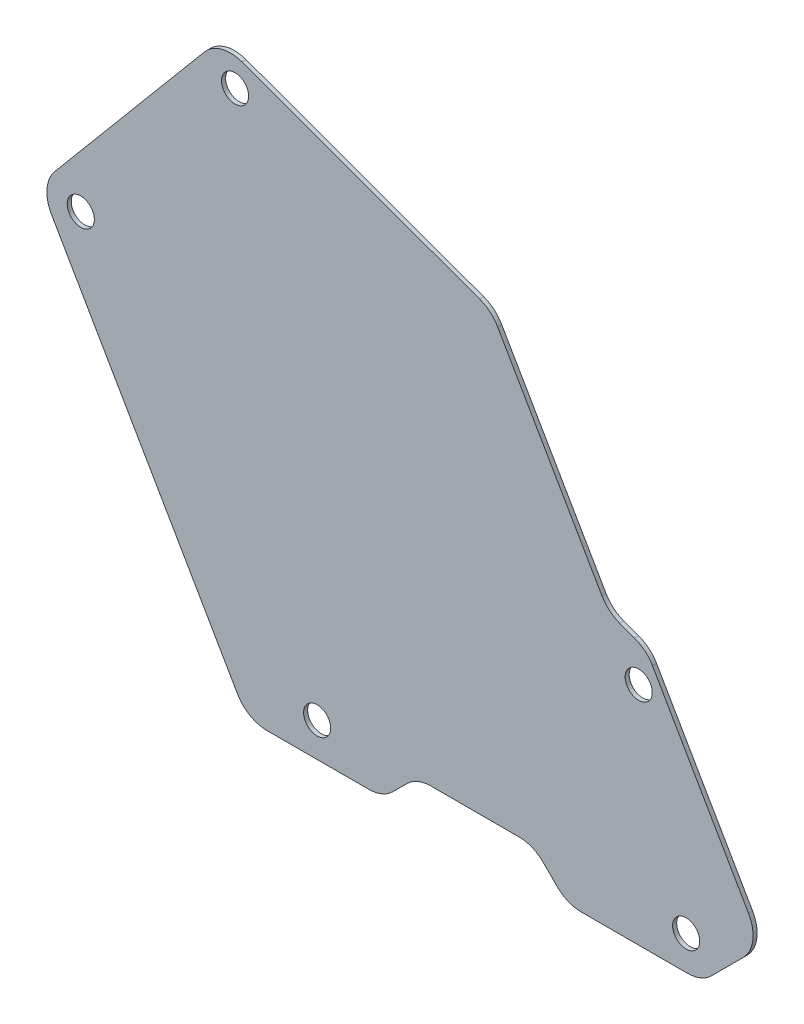
SolidWorks part; units mm, degrees
material "Vidro"
ref_plane "Plano frontal" through (0, 0, 0) normal (0, 0, 1) x (1, 0, 0)
ref_plane "Plano superior" through (0, 0, 0) normal (0, 1, 0) x (1, 0, 0)
ref_plane "Plano direito" through (0, 0, 0) normal (1, 0, 0) x (0, 0, -1)
sketch "Esboço1" plane through (0, 0, 0) normal (0, 0, 1) x (1, 0, 0)
  line L0 (-150, 259.8076) -> (0, 0)
  line L1 (-150, 259.8076) -> (-18.2285, 416.8467)
  line L2 (-23.2285, 418.6666) -> (177.0195, 345.7823)
  line L3 (169.71, 348.4427) -> (259.71, 192.5581)
  line L4 (259.71, 192.5581) -> (287.8295, 182.3235)
  line L5 (287.8295, 182.3235) -> (370, 40)
  line L6 (370, 40) -> (330, 0)
  line L7 (330, 0) -> (235, 0)
  line L8 (210, 25) -> (235, 0)
  line L9 (210, 25) -> (120, 25)
  line L10 (120, 25) -> (95, 0)
  line L11 (95, 0) -> (0, 0)
  line L12 (-156.0806, 260.3396) -> (-86.8301, 140.3942) construction
  line L13 (-150, 259.8076) -> (-80, 138.5641) construction
  line L14 (-18.2285, 416.8467) -> (169.71, 348.4427) construction
  line L16 (-19.8083, 422.7426) -> (173.1302, 352.5187)
  line L17 (173.1302, 352.5187) -> (263.1302, 196.6342)
  line L18 (263.1302, 196.6342) -> (291.2497, 186.3995)
  line L19 (291.2497, 186.3995) -> (376.2484, 39.1774)
  line L20 (376.2484, 39.1774) -> (332.0711, -5)
  line L21 (332.0711, -5) -> (232.9289, -5)
  line L22 (207.9289, 20) -> (232.9289, -5)
  line L23 (207.9289, 20) -> (122.0711, 20)
  line L24 (122.0711, 20) -> (97.0711, -5)
  line L25 (97.0711, -5) -> (-2.8868, -5)
  line L30 (-156.0806, 260.3396) -> (-2.8868, -5)
  line L31 (-156.0806, 260.3396) -> (-19.8083, 422.7426)
  line L32 (-80, 138.5641) -> (-80.433, 138.3141) construction
  line L33 (-80.433, 138.3141) -> (-15.433, 25.7308) construction
  line L34 (-15.433, 25.7308) -> (-15, 25.9808) construction
  line L35 (-17.2631, 18.9006) -> (-16.8301, 19.1506) construction
  line L36 (-87.2631, 140.1442) -> (-17.2631, 18.9006) construction
  line L37 (-86.8301, 140.3942) -> (-87.2631, 140.1442) construction
  line L38 (-15, 25.9808) -> (0, 0) construction
  line L39 (-16.8301, 19.1506) -> (-2.8868, -5) construction
  dimension "D1" = 110
  dimension "D2" = 110
  dimension "D3" = 120
  dimension "D4" = 135
  dimension "D5" = 300
  dimension "D6" = 205
  dimension "D7" = 200
  dimension "D8" = 180
  dimension "D9" = 330
  dimension "D10" = 25
  dimension "D11" = 95
  dimension "D12" = 40
  dimension "D16" = 5
extrude "Ressalto-extrusão1" add sketch "Esboço1" along normal blind 3 contours L11 L10 L9 L8 L7 L6 L5 L4 L3 L2 L1 L0 | L31 L30 L25 L24 L23 L22 L21 L20 L19 L18 L17 L2 L3 L4 L5 L6 L7 L8 L9 L10 L11 L0 L1
fillet "Filete1" radius 25 12 edges at (122.0711, 20, 1.5) (97.0711, -5, 1.5) (207.9289, 20, 1.5) (232.9289, -5, 1.5) (332.0711, -5, 1.5) (376.2484, 39.1774, 1.5) (291.2497, 186.3995, 1.5) (263.1302, 196.6342, 1.5) (-156.0806, 260.3396, 1.5) (-2.8868, -5, 1.5) (177.0195, 345.7823, 1.5) (-23.2285, 418.6666, 1.5)
sketch "Esboço2" plane through (0, 0, 0) normal (0, 0, -1) x (-1, 0, 0)
  circle A0 centre (11.9093, 393.2632) radius 10
  circle A1 centre (125.6774, 257.6797) radius 10
  circle A2 centre (-48.6104, 20) radius 10
  circle A3 centre (-320.6738, 20) radius 10
  circle A4 centre (-285.6738, 161.3195) radius 10
  dimension "D1" = 20
extrude "Corte-extrusão1" cut sketch "Esboço2" against normal through all
